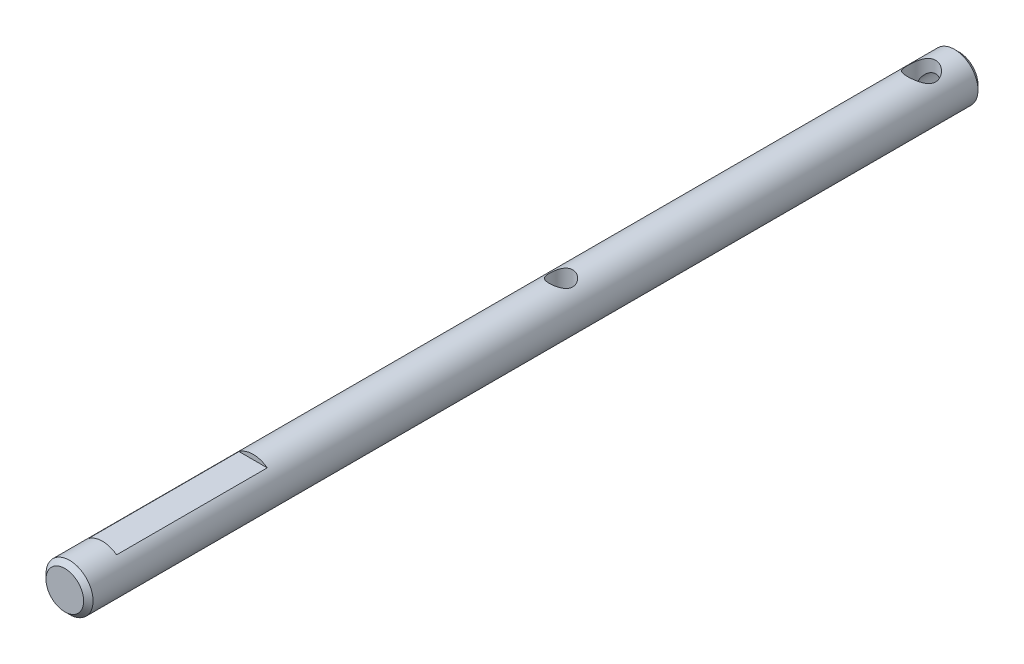
SolidWorks part; units mm, degrees
material "Plain Carbon Steel"
ref_plane "Front Plane" through (0, 0, 0) normal (0, 0, 1) x (1, 0, 0)
ref_plane "Top Plane" through (0, 0, 0) normal (0, 1, 0) x (1, 0, 0)
ref_plane "Right Plane" through (0, 0, 0) normal (1, 0, 0) x (0, 0, -1)
sketch "Sketch1" plane through (0, 0, 0) normal (0, 0, 1) x (1, 0, 0)
  circle A0 centre (0, 0) radius 2.5
  dimension "D1" = 5
extrude "Boss-Extrude1" add sketch "Sketch1" along normal blind 95
sketch "Sketch2" plane through (0, 0, 0) normal (0, 1, 0) x (1, 0, 0)
  line L0 (2.5, 0) -> (-2.5, 0) construction
  line L1 (0, 0) -> (0, -4) construction
  circle A0 centre (0, -4) radius 1.5
  dimension "D1" = 3
  dimension "D2" = 4
extrude "Cut-Extrude1" cut sketch "Sketch2" against normal through all both and the other way through all
chamfer "Chamfer1" distance 0.5 angle 45 2 edges at (2.5, 0, 0) (2.5, 0, 95)
hole_wizard "M3x0.5 Tapped Hole1" positions "Sketch4" profile "Sketch5" tap size "M3x0.5" standard "ANSI Metric"
sketch "Sketch4" plane through (0, 0, 0) normal (0, 0, -1) x (-1, 0, 0)
  point P0 (0, 0)
sketch "Sketch5" plane through (0, 0, 0) normal (1, 0, 0) x (0, 1, 0)
  line L0 (0, 0) -> (0, 2.5)
  line L1 (0, 2.5) -> (1.25, 2.5)
  line L2 (1.25, 2.5) -> (1.25, 0)
  line L5 (1.25, 0) -> (0, 0)
  line L11 (0, -6.35) -> (0, 107.95) construction
  dimension "Thru Tap Drill Dia." = 2.5
  dimension "Thru Tap Drill Depth" = 2.5
cosmetic thread "Hole Thread1"
sketch "Sketch6" plane through (0, 0, 0) normal (1, 0, 0) x (0, 0, -1)
  line L0 (-5.5, 2.5) -> (-94.5, 2.5) construction
  line L1 (-91, 2.5) -> (-75, 2.5)
  line L2 (-91, 2.5) -> (-91, 2)
  line L3 (-91, 2) -> (-75, 2)
  line L4 (-75, 2.5) -> (-75, 2)
  line L5 (-95, 2) -> (-95, -2) construction
  dimension "D1" = 4
  dimension "D2" = 0.5
  dimension "D3" = 16
extrude "Cut-Extrude2" cut sketch "Sketch6" against normal through all both and the other way through all
ref_plane "Plane1" through (0, 3, 0) normal (0, 1, 0) x (1, 0, 0)
sketch "Sketch10" plane through (0, 3, 0) normal (0, 1, 0) x (1, 0, 0)
  line L0 (0, 0) -> (0, -42.3) construction
  line L1 (-2, -95) -> (2, -95) construction
  dimension "D1" = 52.7
hole_wizard "M3x0.5 Tapped Hole2" positions "Sketch11" profile "Sketch12" tap size "M3x0.5" standard "ANSI Metric" end condition through all
sketch "Sketch11" plane through (0, 3, 0) normal (0, 1, 0) x (1, 0, 0)
  point P0 (0, -42.3)
sketch "Sketch12" plane through (0, 3, 42.3) normal (1, 0, 0) x (0, 0, 1)
  line L0 (0, 0) -> (0, 5.5)
  line L1 (0, 5.5) -> (1.25, 5.5)
  line L2 (1.25, 5.5) -> (1.25, 0)
  line L5 (1.25, 0) -> (0, 0)
  line L11 (0, -6.35) -> (0, 107.95) construction
  dimension "Thru Tap Drill Dia." = 2.5
  dimension "Thru Tap Drill Depth" = 5.5
cosmetic thread "Hole Thread2"
